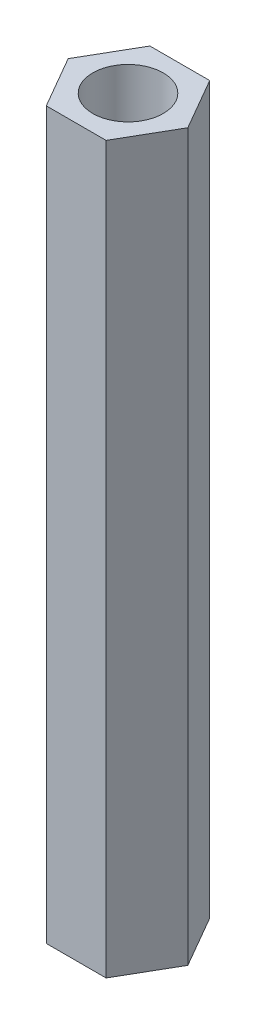
SolidWorks part; units mm, degrees
ref_plane "Front Plane" through (0, 0, 0) normal (0, 0, 1) x (1, 0, 0)
ref_plane "Top Plane" through (0, 0, 0) normal (0, 1, 0) x (1, 0, 0)
ref_plane "Right Plane" through (0, 0, 0) normal (1, 0, 0) x (0, 0, -1)
sketch "Sketch1" plane through (0, 0, 0) normal (0, 1, 0) x (1, 0, 0)
  line L0 (-1.4434, 2.5) -> (1.4434, 2.5)
  line L1 (1.4434, 2.5) -> (2.8868, 0)
  line L2 (2.8868, 0) -> (1.4434, -2.5)
  line L3 (1.4434, -2.5) -> (-1.4434, -2.5)
  line L4 (-1.4434, -2.5) -> (-2.8868, 0)
  line L5 (-2.8868, 0) -> (-1.4434, 2.5)
  circle A0 centre (0, 0) radius 2.5 construction
  point P5 (3.3027, 0)
  point P10 (0, 0)
  point P11 (3.7384, 0)
  point P12 (0, 0)
  point P13 (0, 0)
  point P14 (0, 0)
  point P15 (0, 0)
  point P16 (2.8868, 0)
  dimension "D1" = 5
extrude "Hex Standoff" add sketch "Sketch1" along normal blind 35
sketch "Sketch2" plane through (0, 35, 0) normal (0, 1, 0) x (1, 0, 0)
  circle A0 centre (0, 0) radius 1.5
  point P0 (0, 0)
  dimension "D1" = 3
hole_wizard "M3 Clearance Hole1" positions "Sketch2" profile "Sketch5" hole size "M3" standard "ANSI Metric"
sketch "Sketch5" plane through (0, 35, 0) normal (1, 0, 0) x (0, 0, 1)
  line L0 (0, 0) -> (0, 6.0215)
  line L1 (0, 6.0215) -> (1.7, 5)
  line L2 (1.7, 5) -> (1.7, 0)
  line L5 (1.7, 0) -> (0, 0)
  line L10 (0, 6.0215) -> (-1.7, 5) construction
  line L11 (0, -6.35) -> (0, 107.95) construction
  dimension "Hole Dia." = 3.4
  dimension "Hole Depth" = 5
  dimension "Drill Angle" = 118
sketch "Sketch6" plane through (0, 0, 0) normal (0, -1, 0) x (1, 0, 0)
  circle A0 centre (0, 0) radius 1.5
  point P0 (0, 0)
  dimension "D1" = 3
hole_wizard "M3 Clearance Hole5" positions "Sketch6" profile "Sketch7" hole size "M3" standard "ANSI Metric"
sketch "Sketch7" plane through (0, 0, 0) normal (1, 0, 0) x (0, 0, -1)
  line L0 (0, 0) -> (0, 6.0215)
  line L1 (0, 6.0215) -> (1.7, 5)
  line L2 (1.7, 5) -> (1.7, 0)
  line L5 (1.7, 0) -> (0, 0)
  line L10 (0, 6.0215) -> (-1.7, 5) construction
  line L11 (0, -6.35) -> (0, 107.95) construction
  dimension "Hole Dia." = 3.4
  dimension "Hole Depth" = 5
  dimension "Drill Angle" = 118
